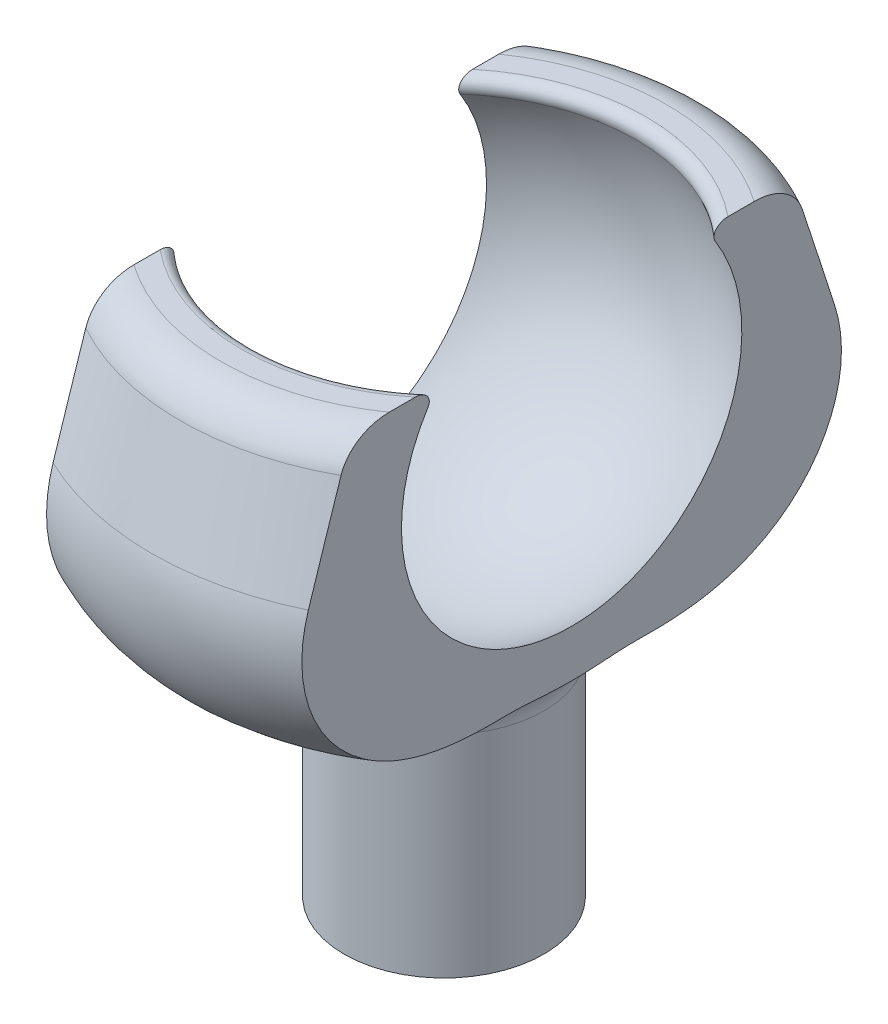
SolidWorks part; units mm, degrees
ref_plane "Alzado" through (0, 0, 0) normal (0, 0, 1) x (1, 0, 0)
ref_plane "Planta" through (0, 0, 0) normal (0, 1, 0) x (1, 0, 0)
ref_plane "Vista lateral" through (0, 0, 0) normal (1, 0, 0) x (0, 0, -1)
sketch "Croquis2" plane through (0, 0, 0) normal (1, 0, 0) x (0, 0, -1)
  line L0 (0, 0) -> (-4.7, 0)
  line L1 (-4.7, 0) -> (-4.7, 9.9021)
  line L5 (0, 12) -> (0, 0)
  line L6 (-10.4688, 27) -> (-9.4868, 27)
  line L7 (0, 22) -> (0, 12) construction
  line L8 (-12.39, 25.5559) -> (-13.7538, 20.8422)
  line L9 (-6.6955, 11.9046) -> (-6.7955, 11.8999)
  arc A1 (0, 12) -> (-9.0351, 26.2857) centre (0, 22) cw
  arc A3 (-4.7, 9.9021) -> (-6.7955, 11.8999) centre (-6.7, 9.9021) ccw
  arc A4 (-13.7538, 20.8422) -> (-6.6955, 11.9046) centre (-7.0296, 18.8967) ccw
  arc A5 (-12.39, 25.5559) -> (-10.4688, 27) centre (-10.4688, 25) cw
  arc A6 (-9.0351, 26.2857) -> (-9.4868, 27) centre (-9.4868, 26.5) ccw
  point P14 (-4.7, 12)
  point P19 (-11.9721, 27)
  point P22 (-8.6603, 27)
  dimension "D2" = 4.7
  dimension "D4" = 10
  dimension "D6" = 2
  dimension "D7" = 7
  dimension "D8" = 2
  dimension "D9" = 0.5
  dimension "D10" = 13.7538
  dimension "D1" = 12
  dimension "D3" = 15
  dimension "D5" = 3.3119
revolve "Revolución1" add sketch "Croquis2" angle 360 about L7
ref_plane "Plano1" through (0, 30, 0) normal (0, 1, 0) x (1, 0, 0)
sketch "Croquis3" plane through (0, 30, 0) normal (0, 1, 0) x (1, 0, 0)
  line L0 (0, 0) -> (0, 18) construction
  line L1 (-18.1558, 18) -> (-6, 18)
  line L2 (-18.1558, 18) -> (-18.1558, -18.6592)
  line L3 (-18.1558, -18.6592) -> (-6, -18.6592)
  line L4 (-6, 18) -> (-6, -18.6592)
  line L5 (18.1558, -18.6592) -> (6, -18.6592)
  line L6 (6, 18) -> (6, -18.6592)
  line L7 (18.1558, 18) -> (6, 18)
  line L8 (18.1558, 18) -> (18.1558, -18.6592)
  dimension "D1" = 18
  dimension "D2" = 6
extrude "Cortar-Extruir1" cut sketch "Croquis3" against normal blind 21
